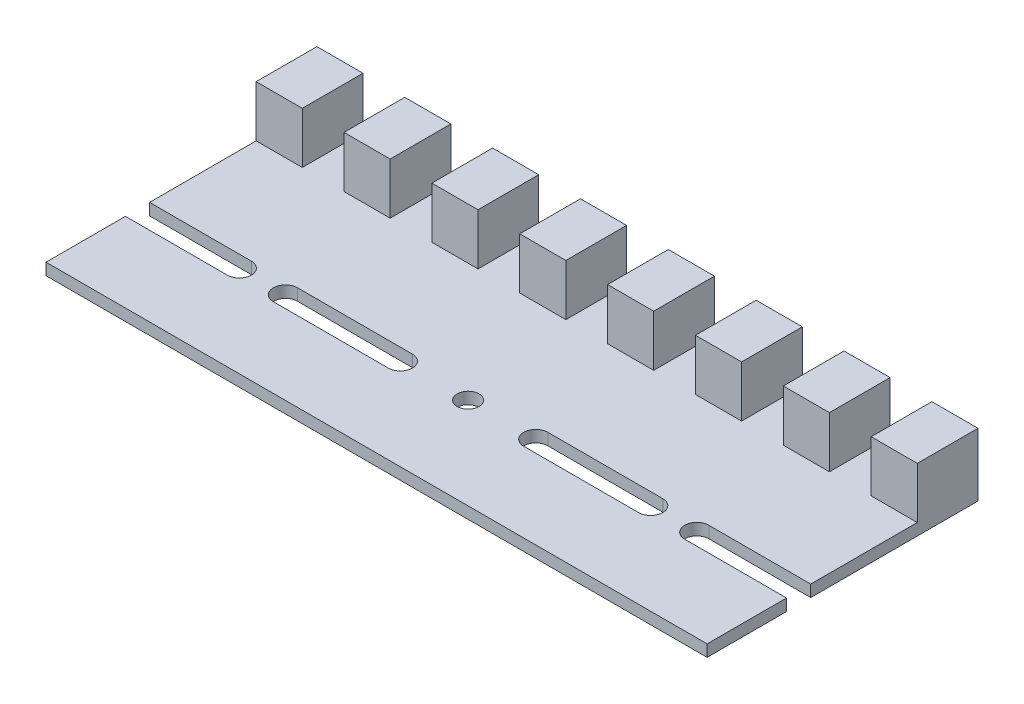
SolidWorks part; units mm, degrees
ref_plane "前视基准面" through (0, 0, 0) normal (0, 0, 1) x (1, 0, 0)
ref_plane "上视基准面" through (0, 0, 0) normal (0, 1, 0) x (1, 0, 0)
ref_plane "右视基准面" through (0, 0, 0) normal (1, 0, 0) x (0, 0, -1)
other "Configuration Table"
sketch "草图1" plane through (0, 0, 0) normal (0, 1, 0) x (1, 0, 0)
  line L1 (-45.15, 18.5) -> (45.15, 18.5)
  line L2 (-45.15, 18.5) -> (-45.15, -18.5)
  line L3 (-45.15, -18.5) -> (45.15, -18.5)
  line L4 (45.15, 18.5) -> (45.15, -18.5)
  line L5 (-45.15, 18.5) -> (45.15, -18.5) construction
  line L6 (-45.15, -18.5) -> (45.15, 18.5) construction
  point P0 (0, 0)
  dimension "D1" = 90.3
  dimension "D2" = 37
extrude "凸台-拉伸1" add sketch "草图1" along normal blind 1.6
sketch "草图2" plane through (0, 1.6, 0) normal (0, 1, 0) x (1, 0, 0)
  line L0 (-45.15, -6) -> (45.15, -6)
  line L1 (-45.15, 18.5) -> (-45.15, -18.5) construction
  line L2 (45.15, -18.5) -> (45.15, 18.5) construction
  line L3 (-45.15, -18.5) -> (45.15, -18.5) construction
  dimension "D1" = 12.5
sketch "草图3" plane through (0, 1.6, 0) normal (0, 1, 0) x (1, 0, 0)
  line L0 (-31.2387, -6) -> (-53.102, -6) construction
  line L1 (-45.15, -6) -> (45.15, -6) construction
  line L2 (-31.2387, -7.65) -> (-53.102, -7.65)
  line L3 (-31.2387, -4.35) -> (-53.102, -4.35)
  line L4 (-24.9447, -6) -> (-9.2447, -6) construction
  line L5 (-24.9447, -4.35) -> (-9.2447, -4.35)
  line L6 (-24.9447, -7.65) -> (-9.2447, -7.65)
  line L7 (0, -6) -> (0, 0) construction
  line L8 (31.2387, -6) -> (53.102, -6) construction
  line L9 (31.2387, -7.65) -> (53.102, -7.65)
  line L10 (31.2387, -4.35) -> (53.102, -4.35)
  line L11 (24.9447, -6) -> (9.2447, -6) construction
  line L12 (24.9447, -4.35) -> (9.2447, -4.35)
  line L13 (24.9447, -7.65) -> (9.2447, -7.65)
  arc A0 (-31.2387, -7.65) -> (-31.2387, -4.35) centre (-31.2387, -6) ccw
  arc A1 (-53.102, -4.35) -> (-53.102, -7.65) centre (-53.102, -6) ccw
  arc A2 (-24.9447, -4.35) -> (-24.9447, -7.65) centre (-24.9447, -6) ccw
  arc A3 (-9.2447, -7.65) -> (-9.2447, -4.35) centre (-9.2447, -6) ccw
  circle A4 centre (0, -6) radius 1.5
  arc A5 (31.2387, -7.65) -> (31.2387, -4.35) centre (31.2387, -6) cw
  arc A6 (53.102, -4.35) -> (53.102, -7.65) centre (53.102, -6) cw
  arc A7 (24.9447, -4.35) -> (24.9447, -7.65) centre (24.9447, -6) cw
  arc A8 (9.2447, -7.65) -> (9.2447, -4.35) centre (9.2447, -6) cw
  point P4 (-42.1703, -6)
  point P9 (-17.0947, -6)
  point P19 (-7.5947, -6)
  point P21 (42.1703, -6)
  point P30 (17.0947, -6)
  dimension "D1" = 3
  dimension "D2" = 3.3
  dimension "D3" = 3.3
  dimension "D4" = 19
extrude "切除-拉伸1" cut sketch "草图3" against normal blind 1.6
sketch "草图4" plane through (0, 1.6, 0) normal (0, 1, 0) x (1, 0, 0)
  line L0 (-26.85, 10.2065) -> (-33.15, 10.2065)
  line L1 (-38.85, 10.2065) -> (-45.15, 10.2065)
  line L2 (-38.85, 10.2065) -> (-38.85, 18.5)
  line L3 (-38.85, 18.5) -> (-45.15, 18.5)
  line L4 (-45.15, 10.2065) -> (-45.15, 18.5)
  line L5 (-38.85, 10.2065) -> (-45.15, 18.5) construction
  line L6 (-38.85, 18.5) -> (-45.15, 10.2065) construction
  line L7 (-26.85, 10.2065) -> (-26.85, 18.5)
  line L8 (-26.85, 18.5) -> (-33.15, 18.5)
  line L9 (-33.15, 10.2065) -> (-33.15, 18.5)
  line L10 (-26.85, 10.2065) -> (-33.15, 18.5) construction
  line L11 (-26.85, 18.5) -> (-33.15, 10.2065) construction
  line L12 (-14.85, 10.2065) -> (-21.15, 10.2065)
  line L13 (-14.85, 10.2065) -> (-14.85, 18.5)
  line L14 (-14.85, 18.5) -> (-21.15, 18.5)
  line L15 (-21.15, 10.2065) -> (-21.15, 18.5)
  line L16 (-14.85, 10.2065) -> (-21.15, 18.5) construction
  line L17 (-14.85, 18.5) -> (-21.15, 10.2065) construction
  line L18 (-2.85, 10.2065) -> (-9.15, 10.2065)
  line L19 (-2.85, 10.2065) -> (-2.85, 18.5)
  line L20 (-2.85, 18.5) -> (-9.15, 18.5)
  line L21 (-9.15, 10.2065) -> (-9.15, 18.5)
  line L22 (-2.85, 10.2065) -> (-9.15, 18.5) construction
  line L23 (-2.85, 18.5) -> (-9.15, 10.2065) construction
  line L24 (9.15, 10.2065) -> (2.85, 10.2065)
  line L25 (9.15, 10.2065) -> (9.15, 18.5)
  line L26 (9.15, 18.5) -> (2.85, 18.5)
  line L27 (2.85, 10.2065) -> (2.85, 18.5)
  line L28 (9.15, 10.2065) -> (2.85, 18.5) construction
  line L29 (9.15, 18.5) -> (2.85, 10.2065) construction
  line L30 (21.15, 10.2065) -> (14.85, 10.2065)
  line L31 (21.15, 10.2065) -> (21.15, 18.5)
  line L32 (21.15, 18.5) -> (14.85, 18.5)
  line L33 (14.85, 10.2065) -> (14.85, 18.5)
  line L34 (21.15, 10.2065) -> (14.85, 18.5) construction
  line L35 (21.15, 18.5) -> (14.85, 10.2065) construction
  line L36 (33.15, 10.2065) -> (26.85, 10.2065)
  line L37 (33.15, 10.2065) -> (33.15, 18.5)
  line L38 (33.15, 18.5) -> (26.85, 18.5)
  line L39 (26.85, 10.2065) -> (26.85, 18.5)
  line L40 (33.15, 10.2065) -> (26.85, 18.5) construction
  line L41 (33.15, 18.5) -> (26.85, 10.2065) construction
  line L42 (45.15, 10.2065) -> (38.85, 10.2065)
  line L43 (45.15, 10.2065) -> (45.15, 18.5)
  line L44 (45.15, 18.5) -> (38.85, 18.5)
  line L45 (38.85, 10.2065) -> (38.85, 18.5)
  line L46 (45.15, 10.2065) -> (38.85, 18.5) construction
  line L47 (45.15, 18.5) -> (38.85, 10.2065) construction
  line L48 (45.15, -4.35) -> (45.15, 18.5) construction
  point P0 (-42, 14.3533)
  point P7 (-30, 14.3533)
  point P12 (-18, 14.3533)
  point P17 (-6, 14.3533)
  point P22 (6, 14.3533)
  point P27 (18, 14.3533)
  point P32 (30, 14.3533)
  point P37 (42, 14.3533)
  dimension "D2" = 12
  dimension "D1" = 8
extrude "凸台-拉伸2" add sketch "草图4" along normal blind 7
